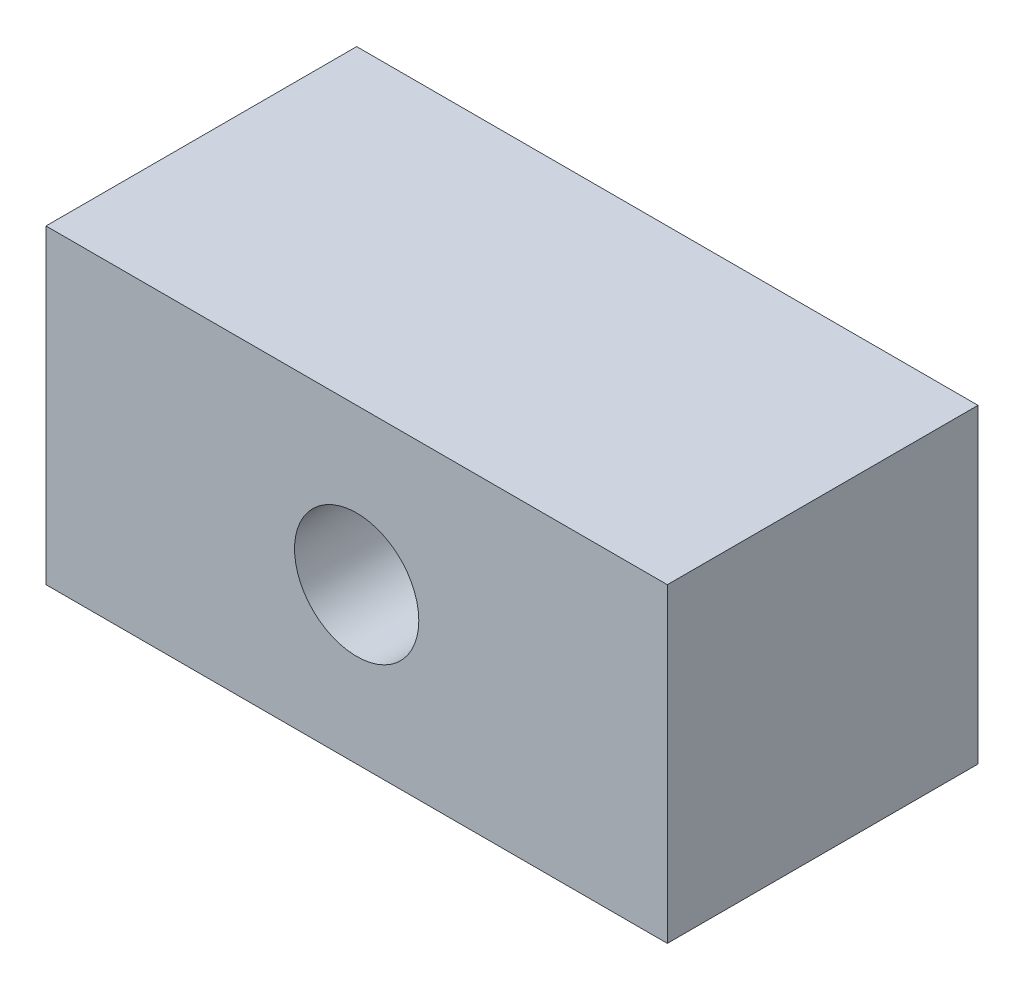
SolidWorks part; units mm, degrees
ref_plane "Plano frontal" through (0, 0, 0) normal (0, 0, 1) x (1, 0, 0)
ref_plane "Plano superior" through (0, 0, 0) normal (0, 1, 0) x (1, 0, 0)
ref_plane "Plano direito" through (0, 0, 0) normal (1, 0, 0) x (0, 0, -1)
sketch "Esboço1" plane through (0, 0, 0) normal (0, 1, 0) x (1, 0, 0)
  line L1 (-20.9615, 4.5192) -> (19.0385, 4.5192)
  line L2 (-20.9615, 4.5192) -> (-20.9615, -15.4808)
  line L3 (-20.9615, -15.4808) -> (19.0385, -15.4808)
  line L4 (19.0385, 4.5192) -> (19.0385, -15.4808)
  dimension "D1" = 40
  dimension "D2" = 20
extrude "Ressalto-extrusão1" add sketch "Esboço1" along normal blind 20
sketch "Esboço2" plane through (0, 0, 15.4808) normal (0, 0, 1) x (1, 0, 0)
  line L0 (-20.9615, 10) -> (19.0385, 10) construction
  line L1 (-20.9615, 20) -> (-20.9615, 0) construction
  line L2 (19.0385, 20) -> (19.0385, 0) construction
  circle A0 centre (-0.9615, 10) radius 4
  dimension "D1" = 8
extrude "Corte-extrusão1" cut sketch "Esboço2" against normal blind 20
